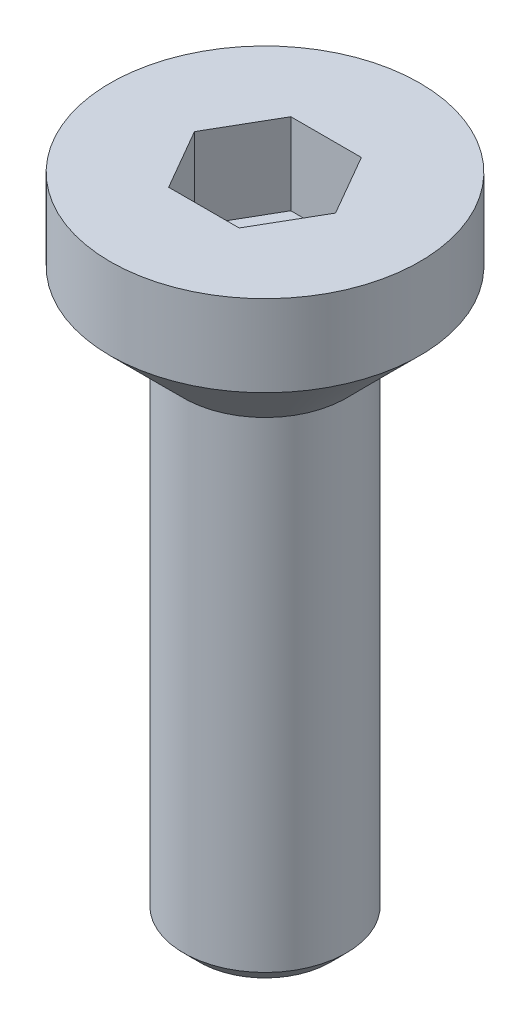
SolidWorks part; units mm, degrees
material "AISI 304"
ref_plane "前视基准面" through (0, 0, 0) normal (0, 0, 1) x (1, 0, 0)
ref_plane "上视基准面" through (0, 0, 0) normal (0, 1, 0) x (1, 0, 0)
ref_plane "右视基准面" through (0, 0, 0) normal (1, 0, 0) x (0, 0, -1)
sketch "草图1" plane through (0, 0, 0) normal (0, 0, 1) x (1, 0, 0)
  line L0 (0, -3.7692) -> (0, 4.9978) construction
  line L1 (0, 3.3297) -> (-1.9, 3.3297)
  line L2 (-1.9, 3.3297) -> (-1.9, 2.3297)
  line L3 (-1.9, 2.3297) -> (-1, 1.4297)
  line L4 (-1, 1.4297) -> (-1, -4.4703)
  line L5 (-1, -4.4703) -> (-0.8, -4.6703)
  line L6 (-0.8, -4.6703) -> (0, -4.6703)
  line L7 (0, -4.6703) -> (0, 3.3297)
  dimension "D1" = 1.9
  dimension "D2" = 1.9
  dimension "D3" = 45
  dimension "D4" = 1
  dimension "D5" = 45
  dimension "D6" = 8
  dimension "D7" = 0.8
revolve "旋转1" add sketch "草图1" angle 360 about L0
sketch "草图2" plane through (0, 3.3297, 0) normal (0, 1, 0) x (1, 0, 0)
  line L1 (-0.433, -0.75) -> (0.433, -0.75)
  line L2 (0.433, -0.75) -> (0.866, 0)
  line L3 (0.866, 0) -> (0.433, 0.75)
  line L4 (0.433, 0.75) -> (-0.433, 0.75)
  line L5 (-0.433, 0.75) -> (-0.866, 0)
  line L6 (-0.866, 0) -> (-0.433, -0.75)
  circle A0 centre (0, 0) radius 0.75 construction
  dimension "D1" = 1.5
extrude "切除-拉伸1" cut sketch "草图2" against normal blind 1
